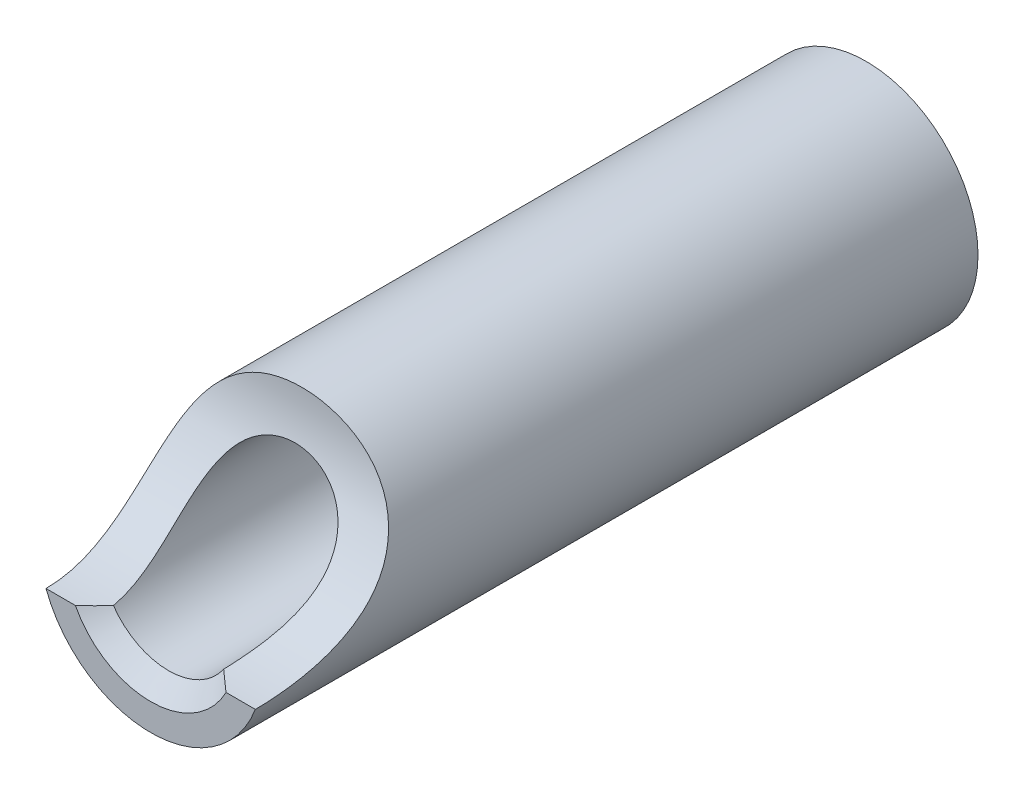
SolidWorks part; units mm, degrees
ref_plane "Front Plane" through (0, 0, 0) normal (0, 0, 1) x (1, 0, 0)
ref_plane "Top Plane" through (0, 0, 0) normal (0, 1, 0) x (1, 0, 0)
ref_plane "Right Plane" through (0, 0, 0) normal (1, 0, 0) x (0, 0, -1)
sketch "Sketch2" plane through (0, 0, 0) normal (0, 0, 1) x (1, 0, 0)
  circle A0 centre (0, 0) radius 4.7625
  circle A1 centre (0, 0) radius 7.9375
  dimension "mouthpiece_outer_diameter" = 15.875
  dimension "mouthpiece_inner_diameter" = 9.525
extrude "tube" add sketch "Sketch2" along normal blind 50.8
chamfer "Chamfer1" distance 1.27 2 edges at (4.7625, 0, 0) (4.7625, 0, 50.8)
sketch "Sketch3" plane through (0, 0, 0) normal (1, 0, 0) x (0, 0, -1)
  line L0 (-50.8, 7.9375) -> (-50.8, -7.9375) construction
  line L1 (0, 7.9375) -> (-50.8, 7.9375) construction
  circle A0 centre (-50.8, 7.9375) radius 10.7274
  dimension "mouthpiece_curved_cut" = 21.4548
extrude "curved_cut" cut sketch "Sketch3" against normal through all both and the other way through all
